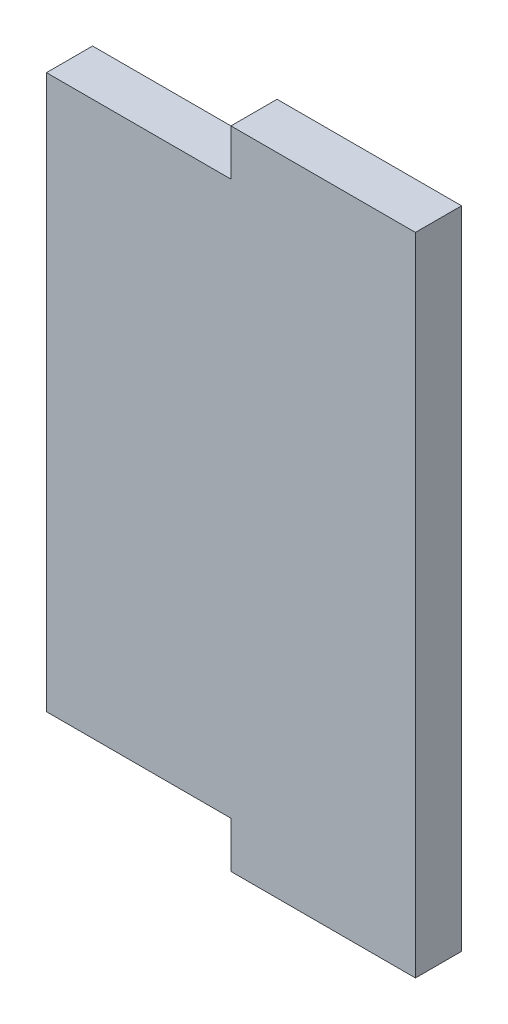
SolidWorks part; units mm, degrees
ref_plane "Front Plane" through (0, 0, 0) normal (0, 0, 1) x (1, 0, 0)
ref_plane "Top Plane" through (0, 0, 0) normal (0, 1, 0) x (1, 0, 0)
ref_plane "Right Plane" through (0, 0, 0) normal (1, 0, 0) x (0, 0, -1)
sketch "Sketch1" plane through (0, 0, 0) normal (0, 0, 1) x (1, 0, 0)
  line L1 (136.525, 0) -> (123.825, 0)
  line L2 (136.525, 0) -> (136.525, -44.45)
  line L3 (136.525, -44.45) -> (123.825, -44.45)
  line L4 (111.125, -3.175) -> (111.125, -41.275)
  line L7 (111.125, -41.275) -> (123.825, -41.275)
  line L8 (123.825, -44.45) -> (123.825, -41.275)
  line L11 (111.125, -3.175) -> (123.825, -3.175)
  line L12 (123.825, 0) -> (123.825, -3.175)
extrude "Boss-Extrude1" add sketch "Sketch1" along normal blind 3.175 contours L2 L3 L8 L7 L4 L11 L12 L1
